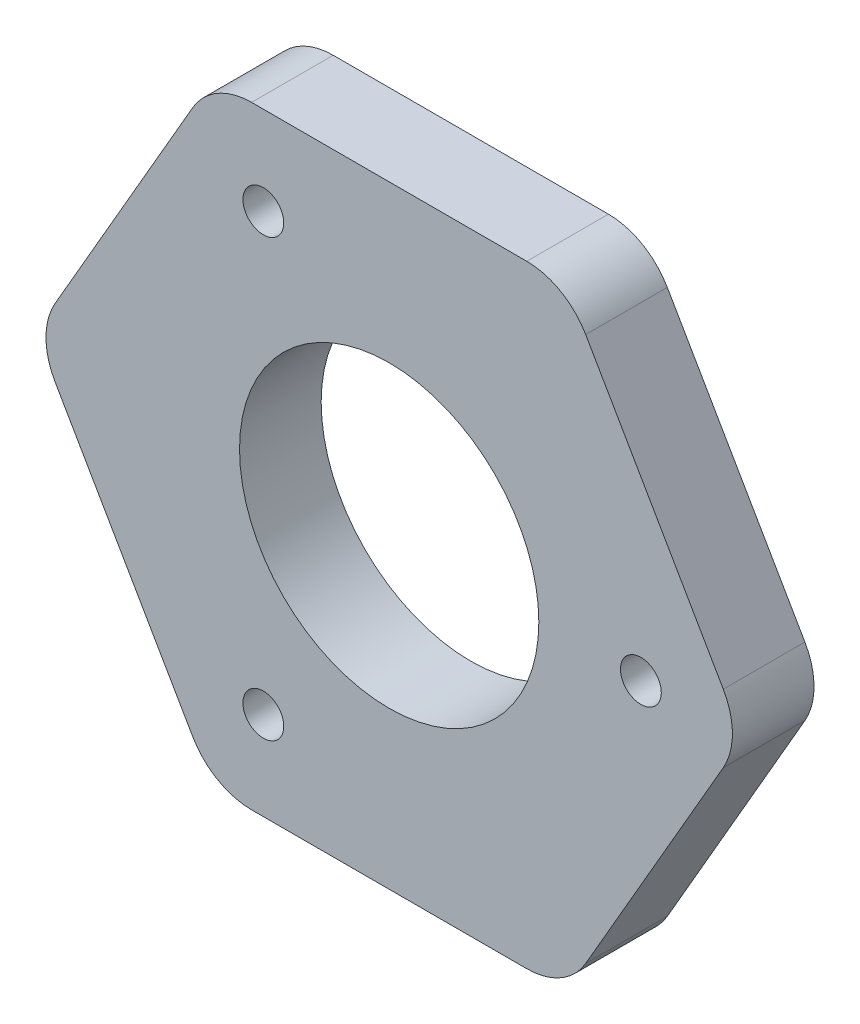
SolidWorks part; units mm, degrees
ref_plane "Front Plane" through (0, 0, 0) normal (0, 0, 1) x (1, 0, 0)
ref_plane "Top Plane" through (0, 0, 0) normal (0, 1, 0) x (1, 0, 0)
ref_plane "Right Plane" through (0, 0, 0) normal (1, 0, 0) x (0, 0, -1)
sketch "Sketch1" plane through (0, 0, 0) normal (0, 0, 1) x (1, 0, 0)
  line L6 (-36.8745, 91.3067) -> (-57.101, 91.3067)
  line L7 (-22.4311, 71.29) -> (-32.5443, 88.8067)
  line L8 (-32.5443, 48.7733) -> (-22.4311, 66.29)
  line L9 (-57.101, 46.2733) -> (-36.8745, 46.2733)
  line L10 (-71.5443, 66.29) -> (-61.4311, 48.7733)
  line L11 (-61.4311, 88.8067) -> (-71.5443, 71.29)
  circle A10 centre (-56.2377, 52.7685) radius 1.5
  circle A11 centre (-28.4877, 68.79) radius 1.5
  circle A12 centre (-46.9877, 68.79) radius 11
  circle A13 centre (-56.2377, 84.8115) radius 1.5
  arc A14 (-57.101, 91.3067) -> (-61.4311, 88.8067) centre (-57.101, 86.3067) ccw
  arc A15 (-32.5443, 88.8067) -> (-36.8745, 91.3067) centre (-36.8745, 86.3067) ccw
  arc A16 (-22.4311, 66.29) -> (-22.4311, 71.29) centre (-26.7612, 68.79) ccw
  arc A17 (-36.8745, 46.2733) -> (-32.5443, 48.7733) centre (-36.8745, 51.2733) ccw
  arc A18 (-61.4311, 48.7733) -> (-57.101, 46.2733) centre (-57.101, 51.2733) ccw
  arc A19 (-71.5443, 71.29) -> (-71.5443, 66.29) centre (-67.2142, 68.79) ccw
  point P1 (0, 0)
  point P3 (0, 0)
  point P5 (0, 0)
  point P7 (0, 0)
  point P22 (0, 0)
  point P25 (0, 0)
  dimension "D5" = 22
  dimension "D9" = 5
  dimension "D15" = 3
  dimension "D16" = 18.5
  dimension "D1" = 20.2265
  dimension "D2" = 60
  dimension "D3" = 60
  dimension "D4" = 60
  dimension "D6" = 32.0429
  dimension "D7" = 32.0429
  dimension "D8" = 32.0429
  dimension "D10" = 60
  dimension "D11" = 60
  dimension "D12" = 46.2733
  dimension "D13" = 46.2733
  dimension "D14" = 36.8745
  dimension "D17" = 18.5
  dimension "D18" = 6.4952
  dimension "D19" = 6.4952
  dimension "D20" = 6.4952
extrude "Boss-Extrude1" add sketch "Sketch1" along normal blind 6 separate body
